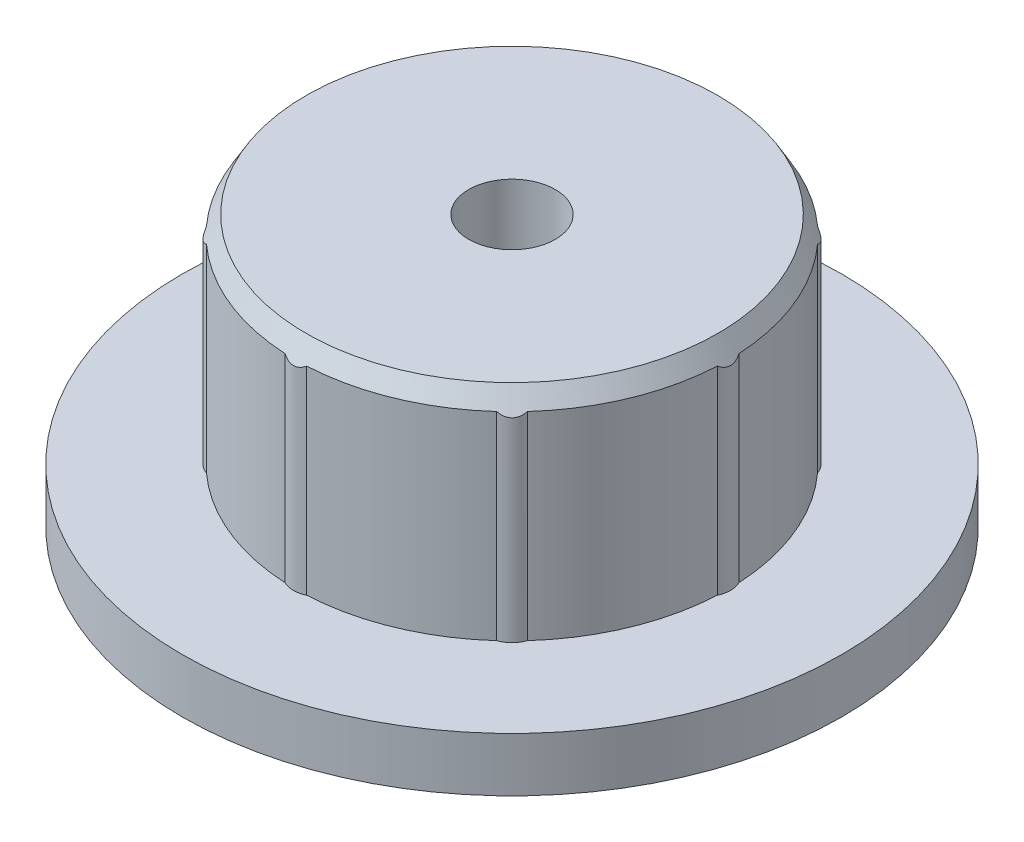
SolidWorks part; units mm, degrees
material "ABS"
ref_plane "Front Plane" through (0, 0, 0) normal (0, 0, 1) x (1, 0, 0)
ref_plane "Top Plane" through (0, 0, 0) normal (0, 1, 0) x (1, 0, 0)
ref_plane "Right Plane" through (0, 0, 0) normal (1, 0, 0) x (0, 0, -1)
sketch "Sketch1" plane through (0, 0, 0) normal (0, 1, 0) x (1, 0, 0)
  line L0 (0, 0) -> (0, 17.8654) construction
  line L1 (0, 0) -> (12.6328, 12.6328) construction
  arc A0 (-1, 19.975) -> (-13.4173, 14.8316) centre (0, 0) ccw
  arc A1 (-1, 19.975) -> (1, 19.975) centre (0, 17.8654) cw
  arc A2 (13.4173, 14.8316) -> (14.8316, 13.4173) centre (12.6328, 12.6328) cw
  arc A3 (19.975, 1) -> (19.975, -1) centre (17.8654, 0) cw
  arc A4 (14.8316, -13.4173) -> (13.4173, -14.8316) centre (12.6328, -12.6328) cw
  arc A5 (1, -19.975) -> (-1, -19.975) centre (0, -17.8654) cw
  arc A6 (-13.4173, -14.8316) -> (-14.8316, -13.4173) centre (-12.6328, -12.6328) cw
  arc A7 (-19.975, -1) -> (-19.975, 1) centre (-17.8654, 0) cw
  arc A8 (-14.8316, 13.4173) -> (-13.4173, 14.8316) centre (-12.6328, 12.6328) cw
  arc A9 (13.4173, 14.8316) -> (1, 19.975) centre (0, 0) ccw
  arc A10 (19.975, 1) -> (14.8316, 13.4173) centre (0, 0) ccw
  arc A11 (14.8316, -13.4173) -> (19.975, -1) centre (0, 0) ccw
  arc A12 (1, -19.975) -> (13.4173, -14.8316) centre (0, 0) ccw
  arc A13 (-13.4173, -14.8316) -> (-1, -19.975) centre (0, 0) ccw
  arc A14 (-19.975, -1) -> (-14.8316, -13.4173) centre (0, 0) ccw
  arc A15 (-14.8316, 13.4173) -> (-19.975, 1) centre (0, 0) ccw
  dimension "D1" = 40
  dimension "D2" = 2
  dimension "D3" = 20.2
  dimension "D5" = 45
  dimension "D4" = 8
extrude "Boss-Extrude1" add sketch "Sketch1" along normal blind 20
sketch "Sketch2" plane through (0, 0, 0) normal (0, 0, 1) x (1, 0, 0)
  line L0 (-18.6123, 20.75) -> (-20.725, 17.0907)
  line L1 (-20.725, 17.0907) -> (-20.725, 20.75)
  line L2 (-20.725, 20.75) -> (-18.6123, 20.75)
  line L3 (-14.8316, 20) -> (-19.975, 20) construction
  line L4 (-19.975, 20) -> (-19.975, 0) construction
  line L5 (0, 0) -> (0, 50000) construction
  dimension "D1" = 30
  dimension "D2" = 0.75
  dimension "D3" = 0.75
  dimension "D4" = 1
revolve "Cut-Revolve1" cut sketch "Sketch2" angle 360 about L5
sketch "Sketch3" plane through (0, 0, 0) normal (0, -1, 0) x (1, 0, 0)
  circle A0 centre (0, 0) radius 30.48
  dimension "D1" = 60.96
extrude "Boss-Extrude2" add sketch "Sketch3" along normal blind 5
sketch "Sketch11" plane through (0, 20, 0) normal (0, 1, 0) x (1, 0, 0)
  circle A0 centre (0, 0) radius 4
  dimension "D1" = 8
extrude "Cut-Extrude2" cut sketch "Sketch11" against normal through all
equation "\"D3@Sketch1\"=40.4/2"
equation "\"D1@Sketch3\"=1.9in+(1/2)*1in"
